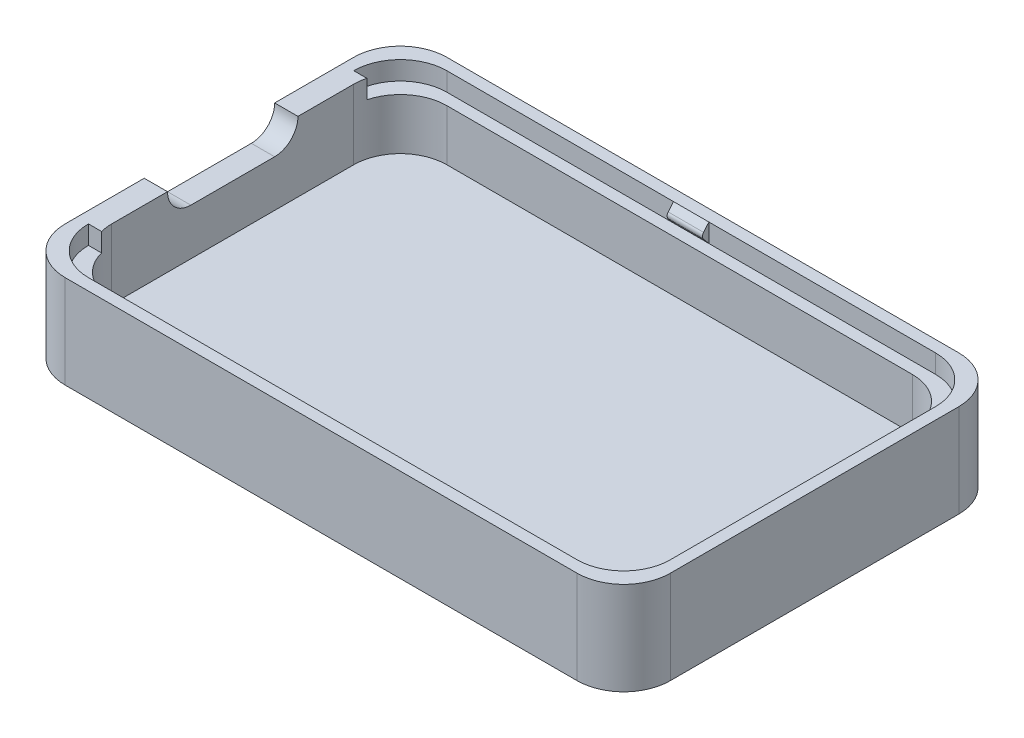
SolidWorks part; units mm, degrees
material "ABS"
ref_plane "Front Plane" through (0, 0, 0) normal (0, 0, 1) x (1, 0, 0)
ref_plane "Top Plane" through (0, 0, 0) normal (0, 1, 0) x (1, 0, 0)
ref_plane "Right Plane" through (0, 0, 0) normal (1, 0, 0) x (0, 0, -1)
sketch "Sketch1" plane through (0, 0, 0) normal (0, 1, 0) x (1, 0, 0)
  line L1 (5, 0) -> (60, 0)
  line L2 (0, 5) -> (0, 36)
  line L3 (5, 41) -> (60, 41)
  line L4 (65, 5) -> (65, 36)
  line L5 (7.5, 38.5) -> (57.5, 38.5)
  line L6 (2.5, 33.5) -> (2.5, 7.5)
  line L7 (7.5, 2.5) -> (57.5, 2.5)
  line L8 (62.5, 33.5) -> (62.5, 7.5)
  arc A0 (60, 41) -> (65, 36) centre (60, 36) cw
  arc A1 (65, 5) -> (60, 0) centre (60, 5) cw
  arc A2 (5, 0) -> (0, 5) centre (5, 5) cw
  arc A3 (0, 36) -> (5, 41) centre (5, 36) cw
  arc A4 (57.5, 38.5) -> (62.5, 33.5) centre (57.5, 33.5) cw
  arc A5 (62.5, 7.5) -> (57.5, 2.5) centre (57.5, 7.5) cw
  arc A6 (7.5, 2.5) -> (2.5, 7.5) centre (7.5, 7.5) cw
  arc A7 (2.5, 33.5) -> (7.5, 38.5) centre (7.5, 33.5) cw
  point P11 (0, 0)
  dimension "D1" = 5
  dimension "D2" = 5
extrude "Boss-Extrude1" add sketch "Sketch1" along normal blind 10
sketch "Sketch2" plane through (0, 0, 0) normal (0, 1, 0) x (1, 0, 0)
  line L1 (7.5, 38.5) -> (57.5, 38.5)
  line L2 (2.5, 33.5) -> (2.5, 7.5)
  line L3 (7.5, 2.5) -> (57.5, 2.5)
  line L4 (62.5, 33.5) -> (62.5, 7.5)
  arc A0 (57.5, 38.5) -> (62.5, 33.5) centre (57.5, 33.5) cw
  arc A1 (62.5, 7.5) -> (57.5, 2.5) centre (57.5, 7.5) cw
  arc A2 (7.5, 2.5) -> (2.5, 7.5) centre (7.5, 7.5) cw
  arc A3 (2.5, 33.5) -> (7.5, 38.5) centre (7.5, 33.5) cw
  dimension "D1" = 5
extrude "Boss-Extrude2" add sketch "Sketch2" along normal blind 2.5
sketch "Sketch3" plane through (0, 0, 0) normal (1, 0, 0) x (0, 0, -1)
  line L0 (36, 10) -> (20.5, 10)
  line L1 (36, 10) -> (5, 10) construction
  line L2 (20.5, 10) -> (13.5, 10)
  line L6 (33.5, 10) -> (7.5, 10) construction
  line L7 (25, 10) -> (16, 10) construction
  line L8 (25, 7.4941) -> (16, 7.4941)
  line L9 (25, 12.5059) -> (16, 12.5059)
  arc A3 (25, 7.4941) -> (25, 12.5059) centre (25, 10) ccw
  arc A4 (16, 12.5059) -> (16, 7.4941) centre (16, 10) ccw
  point P10 (20.5, 10)
ref_plane "Plane1" through (0, 10, 0) normal (0, 1, 0) x (1, 0, 0)
sketch "Sketch4" plane through (0, 10, 0) normal (0, 1, 0) x (1, 0, 0)
  line L1 (6.25, 39.75) -> (58.75, 39.75)
  line L3 (6.25, 1.25) -> (58.75, 1.25)
  line L4 (63.75, 34.75) -> (63.75, 6.25)
  line L5 (7.5, 38.5) -> (57.5, 38.5)
  line L7 (7.5, 2.5) -> (57.5, 2.5)
  line L8 (62.5, 33.5) -> (62.5, 7.5)
  line L9 (1.25, 6.25) -> (2.6588, 6.25)
  line L14 (1.25, 34.75) -> (2.6588, 34.75)
  arc A0 (58.75, 39.75) -> (63.75, 34.75) centre (58.75, 34.75) cw
  arc A1 (63.75, 6.25) -> (58.75, 1.25) centre (58.75, 6.25) cw
  arc A2 (6.25, 1.25) -> (1.25, 6.25) centre (6.25, 6.25) cw
  arc A3 (1.25, 34.75) -> (6.25, 39.75) centre (6.25, 34.75) cw
  arc A4 (57.5, 38.5) -> (62.5, 33.5) centre (57.5, 33.5) cw
  arc A5 (57.5, 2.5) -> (62.5, 7.5) centre (57.5, 7.5) ccw
  arc A6 (7.5, 2.5) -> (2.6588, 6.25) centre (7.5, 7.5) cw
  arc A7 (2.6588, 34.75) -> (7.5, 38.5) centre (7.5, 33.5) cw
  dimension "D1" = 5
  dimension "D2" = 5
extrude "Cut-Extrude2" cut sketch "Sketch4" against normal blind 2
ref_plane "Plane2" through (32.5, 0, 0) normal (1, 0, 0) x (0, 0, -1)
sketch "Sketch5" plane through (32.5, 0, 0) normal (1, 0, 0) x (0, 0, -1)
  line L0 (1.25, 10) -> (1.25, 8)
  line L1 (1.25, 8) -> (1.25, 10) construction
  line L2 (1.25, 8) -> (1.8194, 8.6786)
  line L3 (1.8194, 9.3214) -> (1.25, 10)
  line L7 (39.1806, 9.3214) -> (39.75, 10)
  line L10 (39.75, 8) -> (39.1806, 8.6786)
  line L11 (39.75, 10) -> (39.75, 8)
  arc A0 (39.1806, 8.6786) -> (39.1806, 9.3214) centre (39.5636, 9) cw
  arc A1 (1.8194, 8.6786) -> (1.8194, 9.3214) centre (1.4364, 9) ccw
  dimension "D1" = 0.5
extrude "Boss-Extrude3" add sketch "Sketch5" along normal blind 1.9 and the other way blind 1.9
sketch "Sketch6" plane through (32.5, 0, 0) normal (1, 0, 0) x (0, 0, -1)
  line L1 (5, 0) -> (36, 0) construction
  line L2 (10, 0) -> (8.75, 1.25)
  line L3 (10, 0) -> (7.5, 0)
  line L4 (8.75, 1.25) -> (7.5, 0)
extrude "Cut-Extrude3" cut sketch "Sketch6" against normal blind 5 and the other way blind 5
extrude "Cut-Extrude4" cut sketch "Sketch3" along normal blind 10
